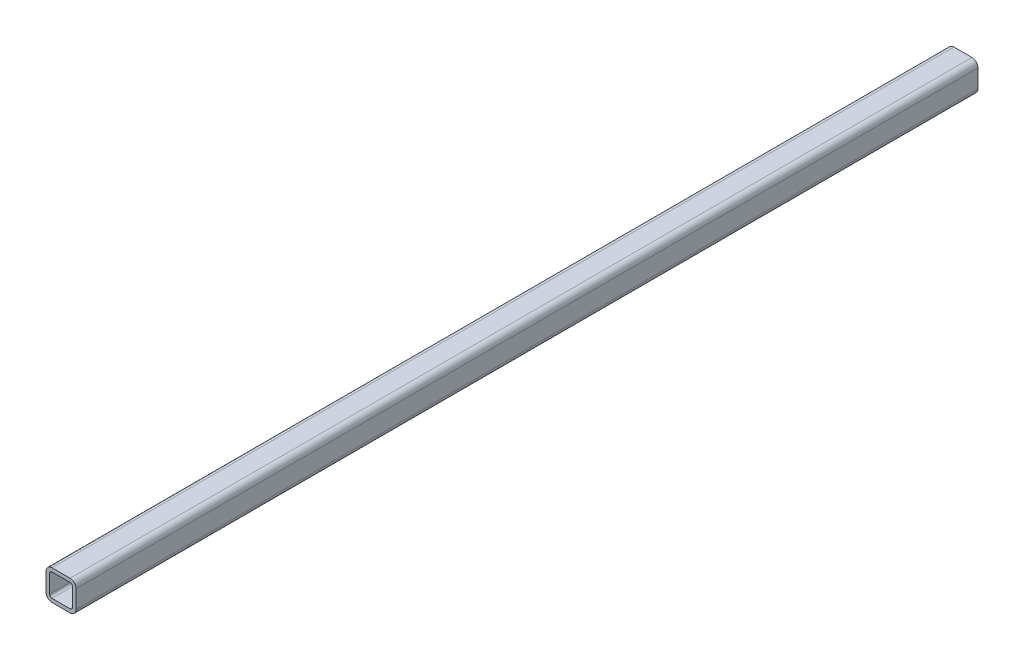
SolidWorks part; units mm, degrees
material "Plain Carbon Steel"
ref_plane "Front Plane" through (0, 0, 0) normal (0, 0, 1) x (1, 0, 0)
ref_plane "Top Plane" through (0, 0, 0) normal (0, 1, 0) x (1, 0, 0)
ref_plane "Right Plane" through (0, 0, 0) normal (1, 0, 0) x (0, 0, -1)
sketch "Sketch1" plane through (0, 0, 0) normal (0, 0, 1) x (1, 0, 0)
  line L0 (-9.5, 7.5) -> (-9.5, -7.5)
  line L1 (-7.5, -12.5) -> (7.5, -12.5)
  line L2 (-12.5, -7.5) -> (-12.5, 7.5)
  line L3 (-7.5, 12.5) -> (7.5, 12.5)
  line L4 (12.5, -7.5) -> (12.5, 7.5)
  line L5 (-12.5, -12.5) -> (12.5, 12.5) construction
  line L6 (-12.5, 12.5) -> (12.5, -12.5) construction
  line L7 (-7.5, -9.5) -> (7.5, -9.5)
  line L8 (9.5, -7.5) -> (9.5, 7.5)
  line L9 (7.5, 9.5) -> (-7.5, 9.5)
  arc A0 (-9.5, -7.5) -> (-7.5, -9.5) centre (-7.5, -7.5) ccw
  arc A1 (7.5, -9.5) -> (9.5, -7.5) centre (7.5, -7.5) ccw
  arc A2 (9.5, 7.5) -> (7.5, 9.5) centre (7.5, 7.5) ccw
  arc A3 (-9.5, 7.5) -> (-7.5, 9.5) centre (-7.5, 7.5) cw
  arc A4 (7.5, 12.5) -> (12.5, 7.5) centre (7.5, 7.5) cw
  arc A5 (7.5, -12.5) -> (12.5, -7.5) centre (7.5, -7.5) ccw
  arc A6 (-7.5, -12.5) -> (-12.5, -7.5) centre (-7.5, -7.5) cw
  arc A7 (-12.5, 7.5) -> (-7.5, 12.5) centre (-7.5, 7.5) cw
  point P0 (0, 0)
  point P12 (-9.5, -9.5)
  point P15 (9.5, -9.5)
  point P18 (9.5, 9.5)
  point P21 (-9.5, 9.5)
  dimension "D4" = 2
  dimension "D5" = 5
  dimension "D1" = 25
  dimension "D2" = 25
  dimension "D3" = 3
extrude "Boss-Extrude1" add sketch "Sketch1" along normal blind 750
